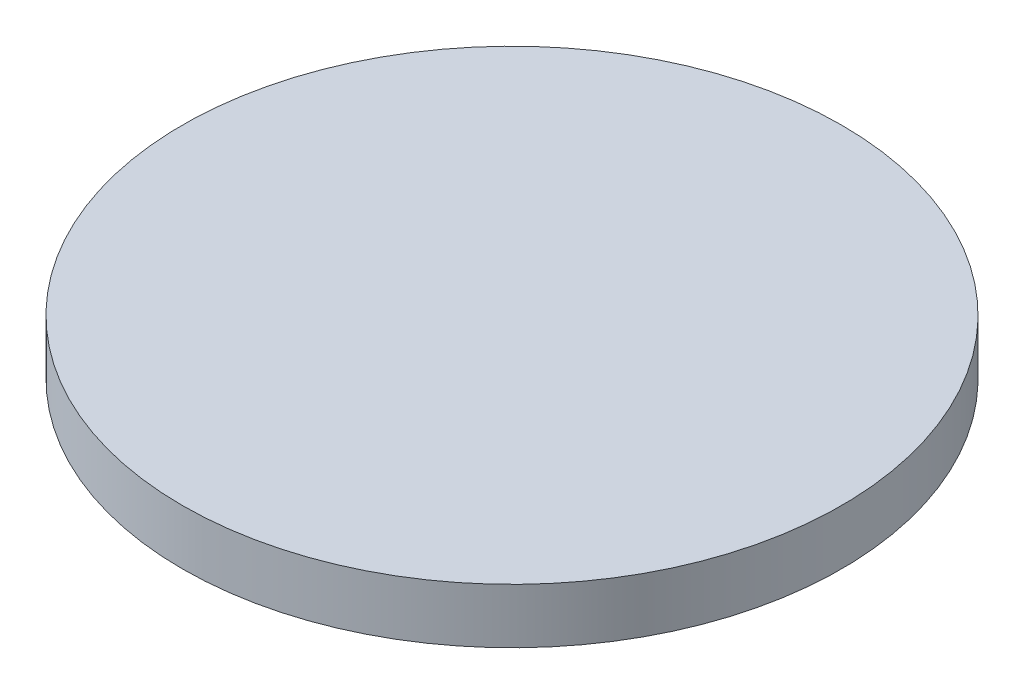
SolidWorks part; units mm, degrees
material "Glass"
ref_plane "Front Plane" through (0, 0, 0) normal (0, 0, 1) x (1, 0, 0)
ref_plane "Top Plane" through (0, 0, 0) normal (0, 1, 0) x (1, 0, 0)
ref_plane "Right Plane" through (0, 0, 0) normal (1, 0, 0) x (0, 0, -1)
sketch "Sketch1" plane through (0, 0, 0) normal (0, 0, 1) x (1, 0, 0)
  line L0 (0, 0) -> (0, 14.3774) construction
  line L1 (-24, 0) -> (-24, 4)
  line L2 (-24, 0) -> (0, 0)
  line L3 (0, 0) -> (0, 4)
  line L4 (0, 4) -> (-24, 4)
  dimension "D1" = 4
  dimension "D2" = 48
revolve "Revolve1" add sketch "Sketch1" angle 360 about L0
